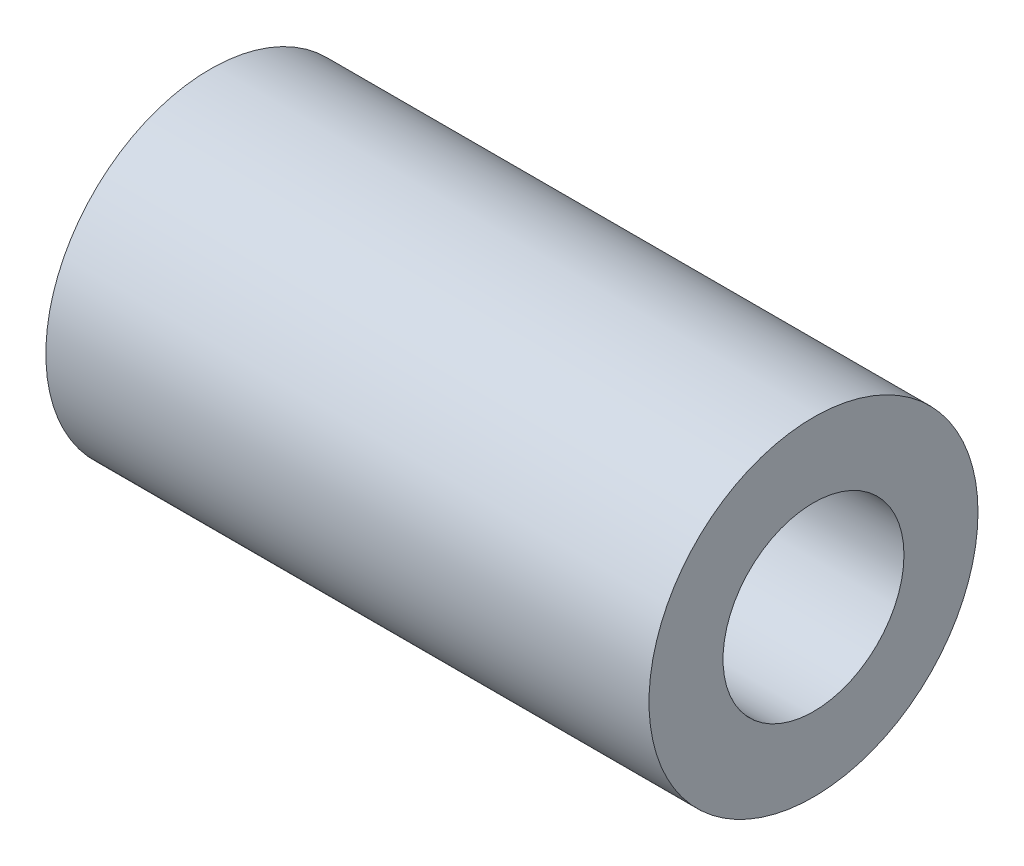
SolidWorks part; units mm, degrees
material "Latão"
ref_plane "Plano frontal" through (0, 0, 0) normal (0, 0, 1) x (1, 0, 0)
ref_plane "Plano superior" through (0, 0, 0) normal (0, 1, 0) x (1, 0, 0)
ref_plane "Plano direito" through (0, 0, 0) normal (1, 0, 0) x (0, 0, -1)
sketch "Esboço1" plane through (0, 0, 0) normal (0, 0, 1) x (1, 0, 0)
  line L0 (0, 0) -> (0, 3)
  line L1 (0, 3) -> (11, 3)
  line L2 (11, 3) -> (11, 0)
  line L5 (11, 0) -> (0, 0)
  dimension "D2" = 11
  dimension "D4" = 3
revolve "Revolução1" add sketch "Esboço1" angle 360 about L5
hole_wizard "Furo roscado de M41" positions "Esboço2" profile "Esboço3" tap size "M4" standard "ISO"
sketch "Esboço2" plane through (11, 0, 0) normal (1, 0, 0) x (0, 0, -1)
  point P0 (0, 0)
sketch "Esboço3" plane through (11, 0, 0) normal (0, 1, 0) x (0, 0, -1)
  line L0 (0, 0) -> (0, 8.9914)
  line L1 (0, 8.9914) -> (1.65, 8)
  line L2 (1.65, 8) -> (1.65, 0)
  line L5 (1.65, 0) -> (0, 0)
  line L10 (0, 8.9914) -> (-1.65, 8) construction
  line L11 (0, -6.35) -> (0, 107.95) construction
  dimension "Tap Drill Dia." = 3.3
  dimension "Tap Drill Depth" = 8
  dimension "Drill Angle" = 118
cosmetic thread "Rosca de furo1"
